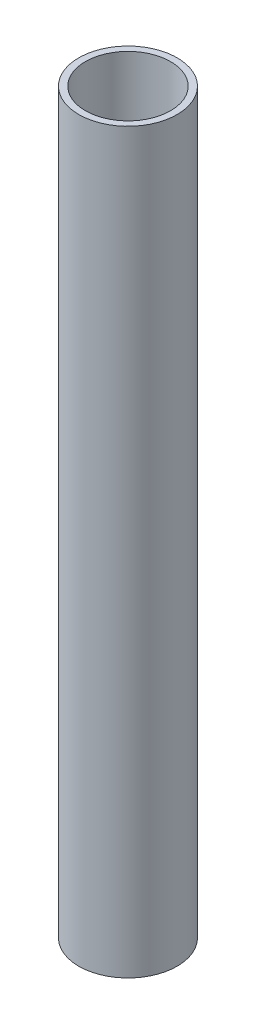
SolidWorks part; units mm, degrees
ref_plane "Front Plane" through (0, 0, 0) normal (0, 0, 1) x (1, 0, 0)
ref_plane "Top Plane" through (0, 0, 0) normal (0, 1, 0) x (1, 0, 0)
ref_plane "Right Plane" through (0, 0, 0) normal (1, 0, 0) x (0, 0, -1)
sketch "Sketch1" plane through (0, 0, 0) normal (0, 1, 0) x (1, 0, 0)
  circle A0 centre (0, 0) radius 2
  dimension "D1" = 4
extrude "Boss-Extrude1" add sketch "Sketch1" along normal blind 30 contours A0
sketch "Sketch4" plane through (0, 30, 0) normal (0, 1, 0) x (1, 0, 0)
  circle A0 centre (0, 0) radius 1.7325
extrude "Cut-Extrude1" cut sketch "Sketch4" against normal blind 30
